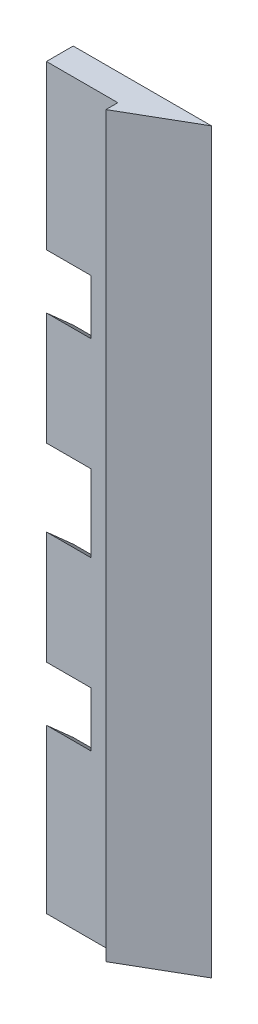
SolidWorks part; units mm, degrees
ref_plane "Front Plane" through (0, 0, 0) normal (1, 0, 0) x (0, 1, 0)
ref_plane "Top Plane" through (0, 0, 0) normal (0, 0, 1) x (0, 1, 0)
ref_plane "Right Plane" through (0, 0, 0) normal (0, 1, 0) x (-1, 0, 0)
sketch "Croquis1" plane through (0, 0, 0) normal (0, 1, 0) x (-1, 0, 0)
  line L0 (0, 0) -> (-18.6, 0)
  line L1 (-18.6, 0) -> (-9.6, 5.2)
  line L3 (0, 4) -> (0, 0)
  line L4 (0, 4) -> (-9.6, 4)
  line L5 (-9.6, 4) -> (-9.6, 5.2)
  dimension "D1" = 18.6
  dimension "D2" = 4
  dimension "D3" = 1.2
  dimension "D4" = 9.6
extrude "BASE" add sketch "Croquis1" against normal blind 99.2
sketch "Croquis2" plane through (0, 0, 0) normal (-1, 0, 0) x (0, -1, 0)
  line L0 (18.35, -0.4) -> (21.925, 3.6)
  line L1 (99.2, 0) -> (0, 0) construction
  line L3 (21.925, 3.6) -> (29.275, 3.6)
  line L4 (29.275, 3.6) -> (32.85, -0.4)
  line L5 (32.85, -0.4) -> (18.35, -0.4)
  line L6 (25.6, -0.4) -> (25.6, 3.6) construction
  line L7 (40.85, -0.4) -> (44.425, 3.6)
  line L8 (44.425, 3.6) -> (54.775, 3.6)
  line L9 (54.775, 3.6) -> (58.35, -0.4)
  line L10 (58.35, -0.4) -> (40.85, -0.4)
  line L11 (49.6, -0.4) -> (49.6, 3.6) construction
  line L12 (69.925, 3.6) -> (66.35, -0.4)
  line L13 (77.275, 3.6) -> (69.925, 3.6)
  line L14 (80.85, -0.4) -> (77.275, 3.6)
  line L15 (66.35, -0.4) -> (80.85, -0.4)
  line L16 (0, 3.6) -> (99.2, 3.6) construction
  line L17 (0, 0) -> (0, 4) construction
  line L18 (99.2, 0) -> (99.2, 4) construction
  line L19 (99.2, 4) -> (0, 4) construction
  line L20 (0, -0.4) -> (99.2, -0.4) construction
  point P22 (18.4033, -0.4)
  point P23 (21.9902, 3.6)
  point P28 (29.2533, 3.6)
  point P29 (40.9, 0)
  point P32 (40.9, 0)
  point P33 (0, 0)
  point P34 (0, 0)
  point P35 (0, 0)
  point P36 (40.8339, -0.4)
  point P37 (44.2694, 3.6)
  point P38 (54.6158, 3.6)
  point P39 (0, 0)
  point P40 (0, 0)
  point P41 (0, 0)
  point P42 (0, 0)
  point P43 (0, 0)
  point P44 (0, 0)
  dimension "D1" = 14.5
  dimension "D2" = 7.35
  dimension "D3" = 17.5
  dimension "D4" = 10.35
  dimension "D5" = 24
  dimension "D6" = 0.4
  dimension "D7" = 0.4
extrude "JOIN_1" cut sketch "Croquis2" against normal blind 6
sketch "Croquis3" plane through (0, 0, 4) normal (0, 0, 1) x (1, 0, 0)
  line L1 (9.6, 0) -> (0, 0)
  line L2 (9.6, 0) -> (9.6, -99.2)
  line L3 (9.6, -99.2) -> (0, -99.2)
  line L4 (0, 0) -> (0, -99.2)
extrude "JOIN_2" cut sketch "Croquis3" against normal blind 0.4
